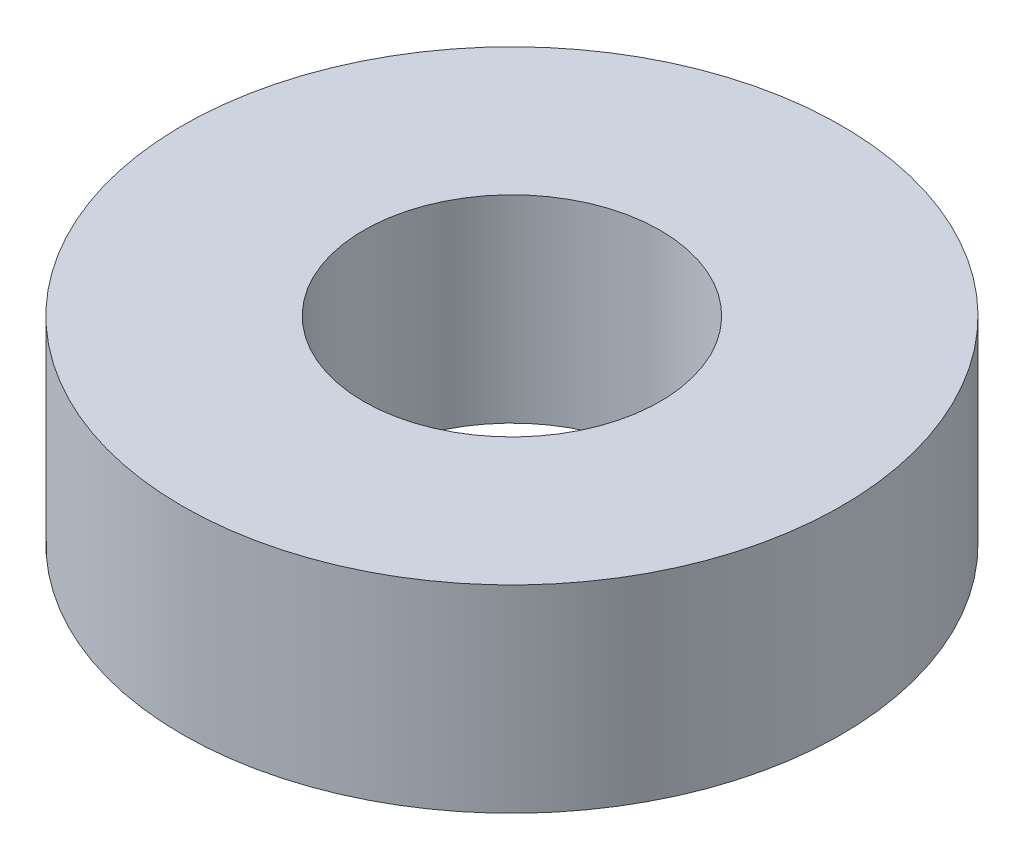
SolidWorks part; units mm, degrees
ref_plane "Alzado" through (0, 0, 0) normal (0, 0, 1) x (1, 0, 0)
ref_plane "Planta" through (0, 0, 0) normal (0, 1, 0) x (1, 0, 0)
ref_plane "Vista lateral" through (0, 0, 0) normal (1, 0, 0) x (0, 0, -1)
sketch "Croquis1" plane through (0, 0, 0) normal (0, 1, 0) x (1, 0, 0)
  circle A0 centre (0, 0) radius 4.5
  circle A1 centre (0, 0) radius 10
  dimension "D1" = 9
  dimension "D2" = 20
extrude "Saliente-Extruir1" add sketch "Croquis1" along normal blind 6
